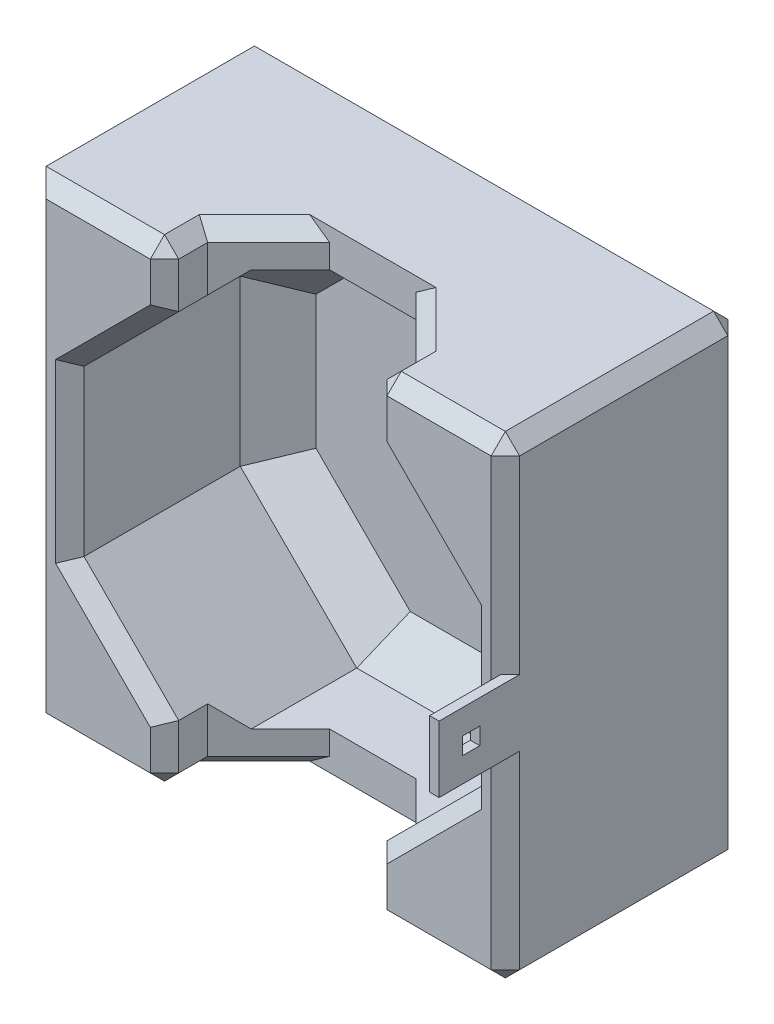
SolidWorks part; units mm, degrees
ref_plane "Front" through (0, 0, 0) normal (0, 0, 1) x (1, 0, 0)
ref_plane "Top" through (0, 0, 0) normal (0, 1, 0) x (1, 0, 0)
ref_plane "Right" through (0, 0, 0) normal (1, 0, 0) x (0, 0, -1)
sketch "Sketch1" plane through (0, 0, 0) normal (0, 0, 1) x (1, 0, 0)
  line L1 (0, 0) -> (50, 0)
  line L2 (0, 0) -> (0, 50)
  line L3 (0, 50) -> (50, 50)
  line L4 (50, 0) -> (50, 50)
  dimension "D1" = 50
extrude "Boss-Extrude1" add sketch "Sketch1" along normal blind 25
sketch "Sketch3" plane through (0, 0, 0) normal (0, -1, 0) x (1, 0, 0)
  line L0 (0, 25) -> (50, 25) construction
  line L1 (36, 29.5563) -> (29.5563, 36)
  line L2 (29.5563, 36) -> (20.4437, 36)
  line L3 (20.4437, 36) -> (14, 29.5563)
  line L4 (14, 29.5563) -> (14, 20.4437)
  line L5 (14, 20.4437) -> (20.4437, 14)
  line L6 (20.4437, 14) -> (29.5563, 14)
  line L7 (29.5563, 14) -> (36, 20.4437)
  line L8 (36, 20.4437) -> (36, 29.5563)
  circle A0 centre (25, 25) radius 11 construction
  dimension "D1" = 22
extrude "Cut-Extrude2" cut sketch "Sketch3" against normal through all
sketch "Sketch5" plane through (0, 0, 25) normal (0, 0, 1) x (1, 0, 0)
  line L0 (25, 50) -> (25, 25) construction
  line L1 (20.4437, 50) -> (29.5563, 50) construction
  line L2 (25, 25) -> (0, 25) construction
  line L3 (0, 50) -> (0, 0) construction
  line L5 (4, 33.6985) -> (4, 16.3015)
  line L6 (4, 16.3015) -> (16.3015, 4)
  line L7 (16.3015, 4) -> (33.6985, 4)
  line L8 (33.6985, 4) -> (46, 16.3015)
  line L9 (46, 16.3015) -> (46, 33.6985)
  line L10 (46, 33.6985) -> (33.6985, 46)
  line L11 (33.6985, 46) -> (16.3015, 46)
  line L12 (16.3015, 46) -> (4, 33.6985)
  circle A1 centre (25, 25) radius 21 construction
  dimension "D1" = 42
extrude "Cut-Extrude3" cut sketch "Sketch5" against normal blind 22
chamfer "Chamfer1" distance 4 angle 45 8 edges at (46, 25, 3) (39.8492, 39.8492, 3) (39.8492, 10.1508, 3) (25, 4, 3) (10.1508, 10.1508, 3) (25, 46, 3) (10.1508, 39.8492, 3) (4, 25, 3)
chamfer "Chamfer2" distance 1.5 angle 45 31 edges at (0, 25, 0) (25, 50, 0) (32.7782, 50, 17.2218) (36, 50, 22.7218) (41, 38.6985, 25) (46, 25, 25) (41, 11.3015, 25) (36, 3.1508, 25) (50, 25, 0) (32.7782, 0, 17.2218) (36, 0, 22.7218) (43, 0, 25) (50, 50, 12.5) (36, 46.8492, 25) (43, 50, 25) (50, 25, 25) (50, 0, 12.5) (25, 0, 0) (17.2218, 0, 17.2218) (14, 0, 22.7218) (17.2218, 50, 17.2218) (14, 50, 22.7218) (9, 38.6985, 25) (14, 46.8492, 25) (7, 50, 25) (9, 11.3015, 25) (14, 3.1508, 25) (0, 25, 25) (0, 0, 12.5) (7, 0, 25) (4, 25, 25)
sketch "Sketch6" plane through (0, 0, 25) normal (0, 0, 1) x (1, 0, 0)
  line L0 (50, 48.5) -> (50, 1.5) construction
  line L1 (50, 28.5) -> (49, 28.5)
  line L2 (50, 28.5) -> (50, 21.5)
  line L3 (50, 21.5) -> (49, 21.5)
  line L4 (49, 28.5) -> (49, 21.5)
  point P6 (50, 25)
  dimension "D1" = 1
  dimension "D2" = 7
extrude "Boss-Extrude2" add sketch "Sketch6" along normal blind 7 and the other way blind 10
sketch "Sketch7" plane through (50, 0, 0) normal (1, 0, 0) x (0, 0, -1)
  line L0 (-29.5, 25) -> (-32, 25) construction
  line L1 (-29.5, 25.9) -> (-27.7, 25.9)
  line L2 (-29.5, 25.9) -> (-29.5, 24.1)
  line L3 (-29.5, 24.1) -> (-27.7, 24.1)
  line L4 (-27.7, 25.9) -> (-27.7, 24.1)
  line L5 (-32, 21.5) -> (-32, 28.5) construction
  dimension "D1" = 2.5
  dimension "D2" = 1.8
extrude "Cut-Extrude4" cut sketch "Sketch7" against normal through all
